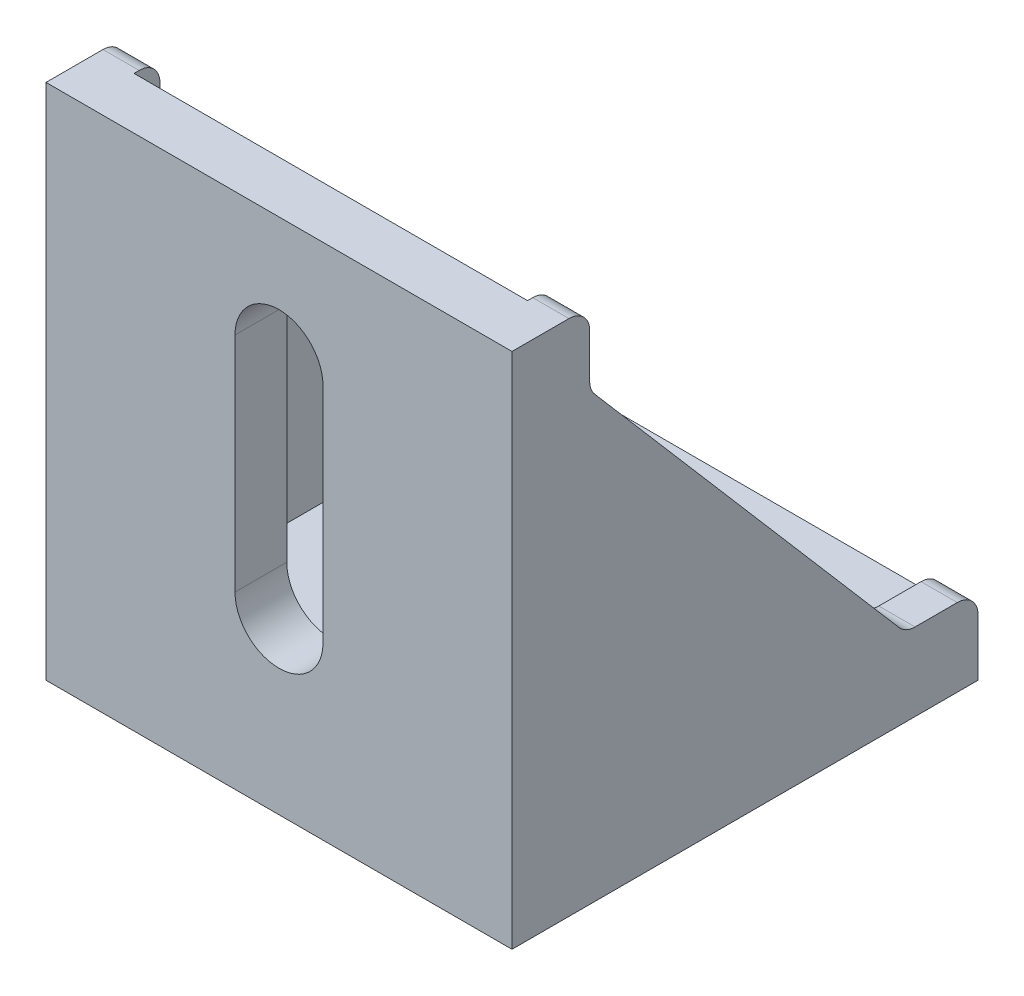
SolidWorks part; units mm, degrees
ref_plane "前视基准面" through (0, 0, 0) normal (0, 0, 1) x (1, 0, 0)
ref_plane "上视基准面" through (0, 0, 0) normal (0, 1, 0) x (1, 0, 0)
ref_plane "右视基准面" through (0, 0, 0) normal (1, 0, 0) x (0, 0, -1)
other "Configuration Table"
sketch "草图1" plane through (0, 0, 0) normal (1, 0, 0) x (0, 0, -1)
  line L0 (0, 0) -> (0, 45)
  line L2 (0, 0) -> (0, -5)
  line L3 (0, -5) -> (45, -5)
  line L4 (45, 0) -> (45, -5)
  line L5 (0, 45) -> (5, 45)
  line L6 (45, 0) -> (5, 0)
  line L7 (5, 0) -> (5, 45)
  dimension "D1" = 45
  dimension "D2" = 5
  dimension "D3" = 45
  dimension "D4" = 5
extrude "凸台-拉伸1" add sketch "草图1" along normal blind 45
sketch "草图2" plane through (45, 0, 0) normal (1, 0, 0) x (0, 0, -1)
  line L0 (45, 0) -> (45, 2.5)
  line L1 (45, 2.5) -> (38, 2.5)
  line L2 (5, 45) -> (7.5, 45)
  line L3 (7.5, 45) -> (7.5, 38)
  line L4 (7.5, 38) -> (38, 2.5)
  line L5 (5, 45) -> (5, 0)
  line L6 (5, 0) -> (45, 0)
  dimension "D1" = 2.5
  dimension "D2" = 7
  dimension "D3" = 2.5
  dimension "D4" = 7
extrude "凸台-拉伸2" add sketch "草图2" against normal blind 3.5
ref_plane "基准面1" through (22.5, 0, 0) normal (1, 0, 0) x (0, 0, -1)
mirror "镜向1" about plane through (22.5, 0, 0) normal (1, 0, 0) of "凸台-拉伸2"
sketch "草图4" plane through (0, 0, -5) normal (0, 0, -1) x (-1, 0, 0)
  line L0 (-22.5, 33) -> (-22.5, 11.5) construction
  line L1 (-22.5, 22) -> (-22.5, -22) construction
  line L2 (-18.25, 33) -> (-18.25, 11.5)
  line L3 (-26.75, 33) -> (-26.75, 11.5)
  line L5 (-41.5, 45) -> (-3.5, 45) construction
  arc A0 (-18.25, 33) -> (-26.75, 33) centre (-22.5, 33) ccw
  arc A1 (-26.75, 11.5) -> (-18.25, 11.5) centre (-22.5, 11.5) ccw
  point P4 (-22.5, 22.25)
  point P11 (-22.5, 37.25)
  point P12 (-22.5, 7.25)
  dimension "D1" = 30
  dimension "D2" = 8.5
  dimension "D3" = 12
extrude "切除-拉伸1" cut sketch "草图4" against normal up to next
sketch "草图5" plane through (0, 0, 0) normal (0, 1, 0) x (1, 0, 0)
  line L0 (22.5, 37) -> (22.5, 15.5) construction
  line L1 (22.5, -22) -> (22.5, 22) construction
  line L2 (26.75, 37) -> (26.75, 15.5)
  line L3 (18.25, 37) -> (18.25, 15.5)
  line L4 (41.5, 45) -> (3.5, 45) construction
  arc A0 (26.75, 37) -> (18.25, 37) centre (22.5, 37) ccw
  arc A1 (18.25, 15.5) -> (26.75, 15.5) centre (22.5, 15.5) ccw
  point P4 (22.5, 26.25)
  point P9 (22.5, 11.25)
  point P10 (22.5, 41.25)
  dimension "D1" = 30
  dimension "D2" = 8.5
  dimension "D3" = 8
extrude "切除-拉伸2" cut sketch "草图5" against normal up to next
fillet "圆角1" radius 2 8 edges at (1.75, 38, -7.5) (1.75, 45, -7.5) (43.25, 45, -7.5) (43.25, 38, -7.5) (43.25, 2.5, -38) (1.75, 2.5, -38) (1.75, 2.5, -45) (43.25, 2.5, -45)
